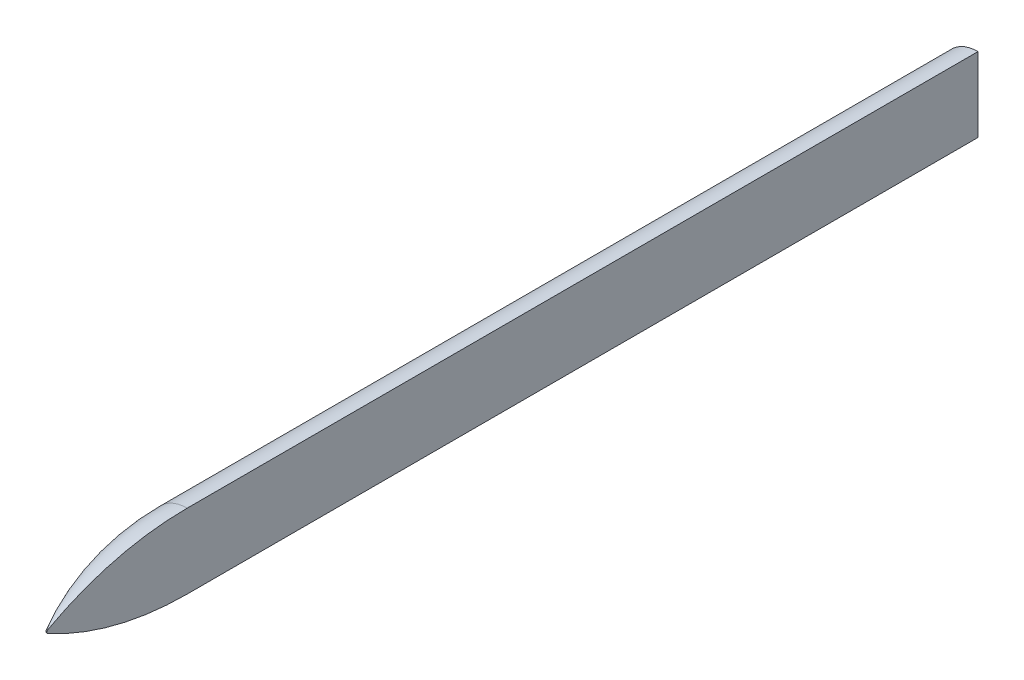
SolidWorks part; units mm, degrees
ref_plane "Front Plane" through (0, 0, 0) normal (0, 0, 1) x (1, 0, 0)
ref_plane "Top Plane" through (0, 0, 0) normal (0, 1, 0) x (1, 0, 0)
ref_plane "Right Plane" through (0, 0, 0) normal (1, 0, 0) x (0, 0, -1)
sketch "Sketch1" plane through (0, 0, 0) normal (1, 0, 0) x (0, 0, -1)
  line L0 (500, 40) -> (-350, 40)
  line L1 (0, 0) -> (-953.775, 0) construction
  line L2 (500, 40) -> (500, 0)
  line L3 (-501, 0) -> (500, 0)
  arc A0 (-350, 40) -> (-500, 1.6861) centre (-350, -272.7841) ccw
  arc A1 (-500, 1.6861) -> (-501, 0) centre (-499.0785, 0) ccw
  point P6 (0, 0)
  point P9 (-501, 0)
  point P12 (-500, 5)
  dimension "D1" = 1000
  dimension "D2" = 150
  dimension "D3" = 40
  dimension "D5" = 1
  dimension "D6" = 500
revolve "Revolve1" add sketch "Sketch1" angle 180 about L1
equation "\"Lenghtreference\" = 1000"
equation "\"D6@Sketch1\"=\"Lenghtreference\"/2"
equation "\"D1@Sketch1\"=\"Lenghtreference\""
equation "\"Diameter\"=80"
equation "\"D3@Sketch1\"=\"Diameter\"/2"
